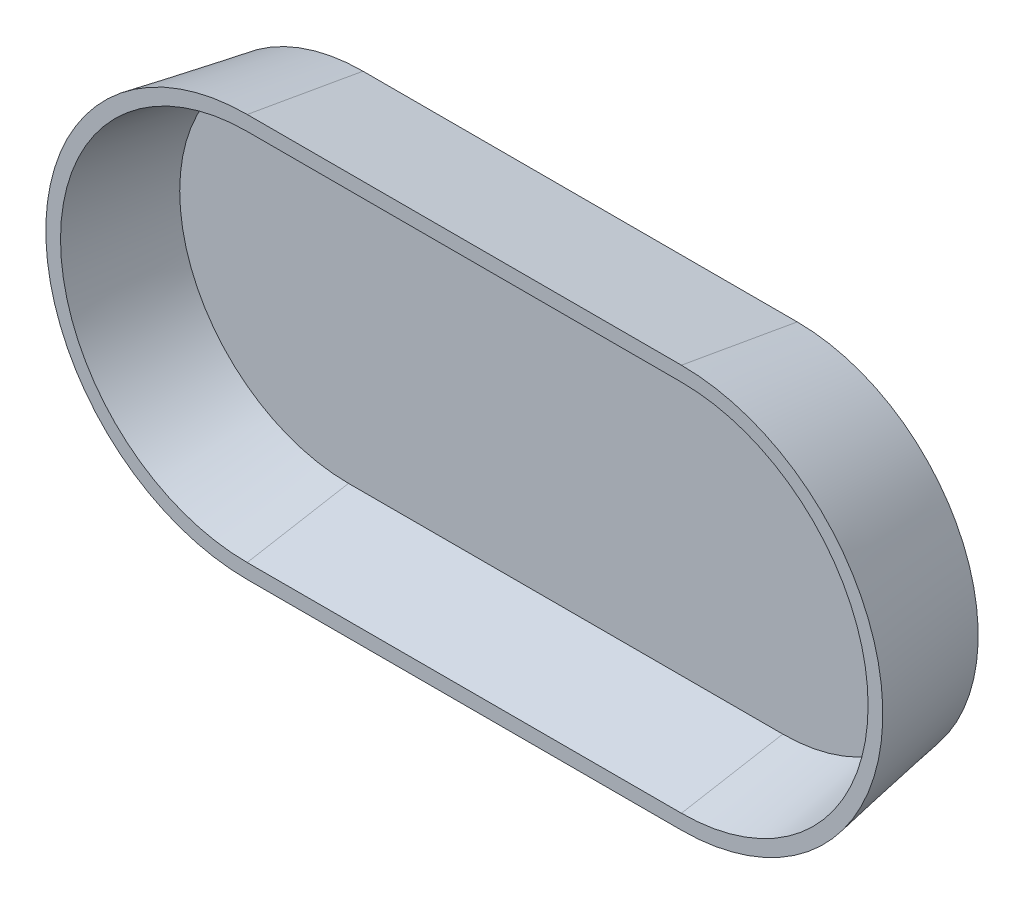
SolidWorks part; units mm, degrees
ref_plane "Front Plane" through (0, 0, 0) normal (0, 0, 1) x (1, 0, 0)
ref_plane "Top Plane" through (0, 0, 0) normal (0, 1, 0) x (1, 0, 0)
ref_plane "Right Plane" through (0, 0, 0) normal (1, 0, 0) x (0, 0, -1)
sketch "Sketch1" plane through (0, 0, 0) normal (0, 0, 1) x (1, 0, 0)
  line L0 (0, 0) -> (-30, 0) construction
  line L1 (0, -12.5) -> (-30, -12.5)
  line L2 (0, 12.5) -> (-30, 12.5)
  arc A0 (0, -12.5) -> (0, 12.5) centre (0, 0) ccw
  arc A1 (-30, 12.5) -> (-30, -12.5) centre (-30, 0) ccw
  point P3 (-15, 0)
  dimension "D1" = 30
  dimension "D2" = 25
extrude "Boss-Extrude1" add sketch "Sketch1" along normal blind 8 draft 10 draft outward yes
shell "Shell1" thickness 1
